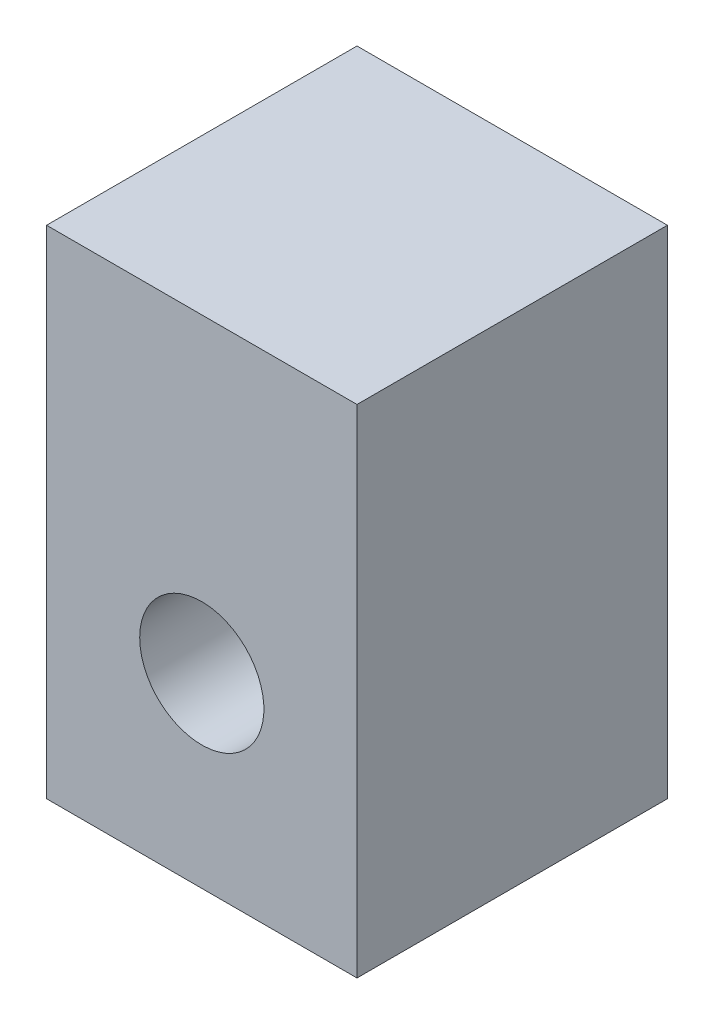
SolidWorks part; units mm, degrees
ref_plane "Front Plane" through (0, 0, 0) normal (0, 0, 1) x (1, 0, 0)
ref_plane "Top Plane" through (0, 0, 0) normal (0, 1, 0) x (1, 0, 0)
ref_plane "Right Plane" through (0, 0, 0) normal (1, 0, 0) x (0, 0, -1)
sketch "Sketch1" plane through (0, 0, 0) normal (0, 0, -1) x (-1, 0, 0)
  line L1 (74.54, 62.5) -> (84.54, 62.5)
  line L2 (74.54, 62.5) -> (74.54, 46.5)
  line L3 (74.54, 46.5) -> (84.54, 46.5)
  line L4 (84.54, 62.5) -> (84.54, 46.5)
  circle A0 centre (79.54, 52.5) radius 2 construction
  circle A1 centre (79.54, 52.5) radius 2
extrude "Boss-Extrude1" add sketch "Sketch1" against normal blind 10
